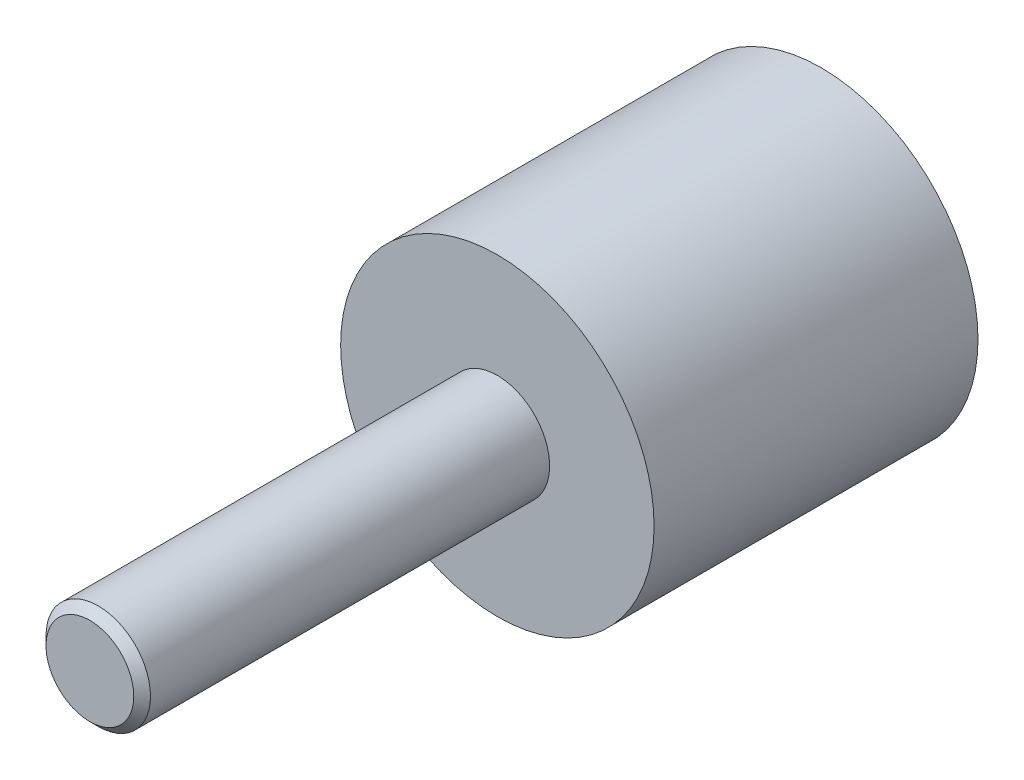
SolidWorks part; units mm, degrees
material "6061 Alloy"
ref_plane "Front Plane" through (0, 0, 0) normal (0, 0, 1) x (1, 0, 0)
ref_plane "Top Plane" through (0, 0, 0) normal (0, 1, 0) x (1, 0, 0)
ref_plane "Right Plane" through (0, 0, 0) normal (1, 0, 0) x (0, 0, -1)
sketch "Sketch" plane through (0, 0, 0) normal (1, 0, 0) x (0, 0, -1)
  line L0 (0, 0) -> (0, 3.175)
  line L1 (0, 3.175) -> (24.765, 3.175)
  line L2 (24.765, 3.175) -> (24.765, 9.525)
  line L3 (24.765, 9.525) -> (44.45, 9.525)
  line L4 (44.45, 9.525) -> (44.45, 0)
  line L7 (44.45, 0) -> (0, 0)
  dimension "D1" = 3.175
  dimension "D3" = 9.525
  dimension "D5" = 19.685
  dimension "D6" = 44.45
revolve "Shaft" add sketch "Sketch" angle 360 about L7
hole_wizard "1/2 (0.5) Diameter Hole2" positions "Sketch7" profile "Sketch6" hole size "1/2" standard "ANSI Inch"
sketch "Sketch7" plane through (0, 0, -44.45) normal (0, 0, -1) x (-1, 0, 0)
  point P0 (0, 0)
sketch "Sketch6" plane through (0, 0, -44.45) normal (1, 0, 0) x (0, 1, 0)
  line L0 (0, 0) -> (0, 16.5155)
  line L1 (0, 16.5155) -> (6.35, 12.7)
  line L2 (6.35, 12.7) -> (6.35, 0)
  line L5 (6.35, 0) -> (0, 0)
  line L10 (0, 16.5155) -> (-6.35, 12.7) construction
  line L11 (0, -6.35) -> (0, 107.95) construction
  dimension "Hole Dia." = 12.7
  dimension "Hole Depth" = 12.7
  dimension "Drill Angle" = 118
ref_plane "Set Screw Reference Plane" through (0, -9.525, 0) normal (0, -1, 0) x (-1, 0, 0)
hole_wizard "#4-40 Tapped Hole1" positions "Sketch3" profile "Sketch2" tap size "#4-40" standard "ANSI Inch"
sketch "Sketch3" plane through (0, -9.525, 0) normal (0, -1, 0) x (-1, 0, 0)
  line L3 (9.525, 44.45) -> (-9.525, 44.45) construction
  line L4 (0, 24.765) -> (0, 44.45) construction
  line L5 (-9.525, 24.765) -> (9.525, 24.765) construction
  point P8 (0, 34.925)
  point P10 (0, 41.275)
  dimension "D1" = 3.175
  dimension "D2" = 9.525
sketch "Sketch2" plane through (0, -9.525, -34.925) normal (1, 0, 0) x (0, 0, -1)
  line L0 (0, 0) -> (0, 3.175)
  line L1 (0, 3.175) -> (1.1303, 3.175)
  line L2 (1.1303, 3.175) -> (1.1303, 0)
  line L5 (1.1303, 0) -> (0, 0)
  line L11 (0, -6.35) -> (0, 107.95) construction
  dimension "Thru Tap Drill Dia." = 2.2606
  dimension "Thru Tap Drill Depth" = 3.175
cosmetic thread "Hole Thread1" parameters "D1"=0, "D2"=3.2606
cosmetic thread "Hole Thread2" parameters "D1"=0, "D2"=3.2606
chamfer "Chamfer1" distance 0.508 angle 45 2 edges at (-6.35, 0, -44.45) (-3.175, 0, 0)
